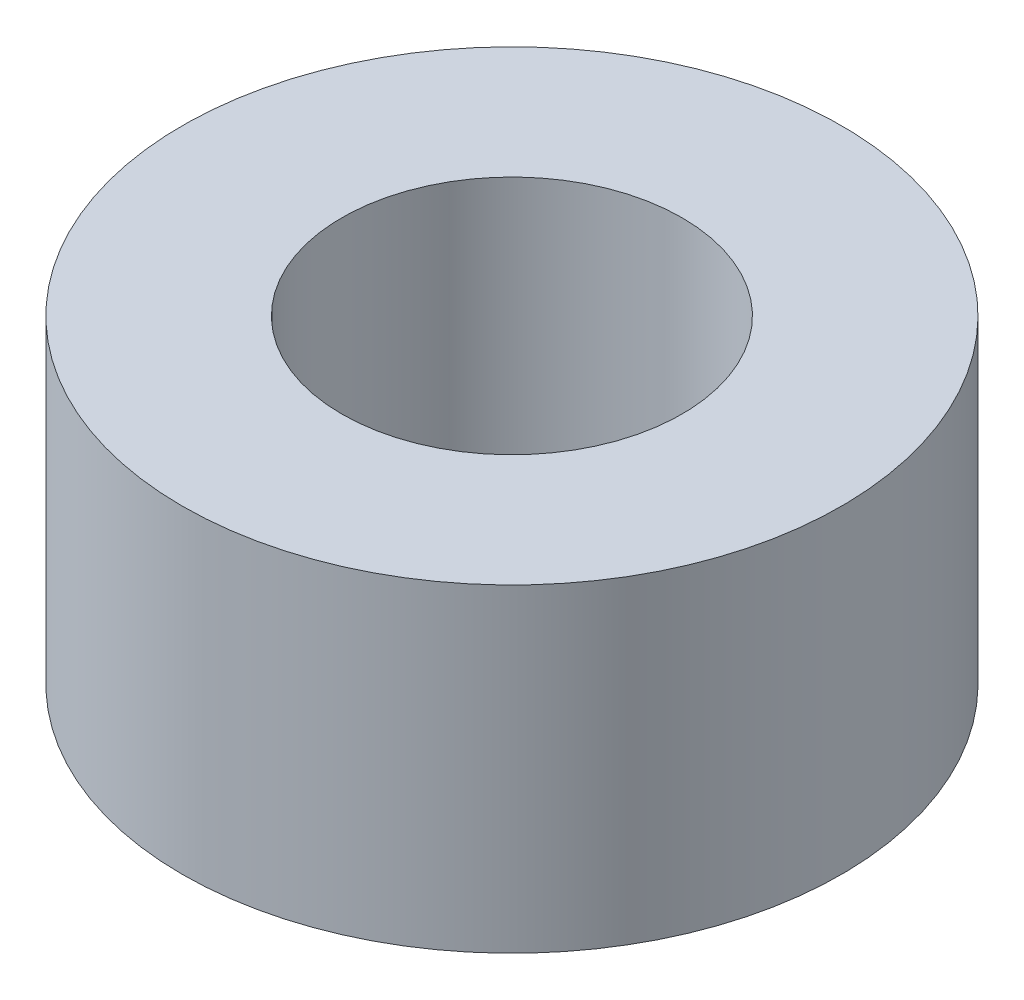
SolidWorks part; units mm, degrees
ref_plane "Plan de face" through (0, 0, 0) normal (0, 0, 1) x (1, 0, 0)
ref_plane "Plan de dessus" through (0, 0, 0) normal (0, 1, 0) x (1, 0, 0)
ref_plane "Plan de droite" through (0, 0, 0) normal (1, 0, 0) x (0, 0, -1)
sketch "Esquisse1" plane through (0, 0, 0) normal (0, 1, 0) x (1, 0, 0)
  circle A0 centre (0, 0) radius 1.6
  circle A1 centre (0, 0) radius 3.1
  dimension "D1" = 3.2
  dimension "D2" = 1.5
extrude "Boss.-Extru.1" add sketch "Esquisse1" along normal blind 3
